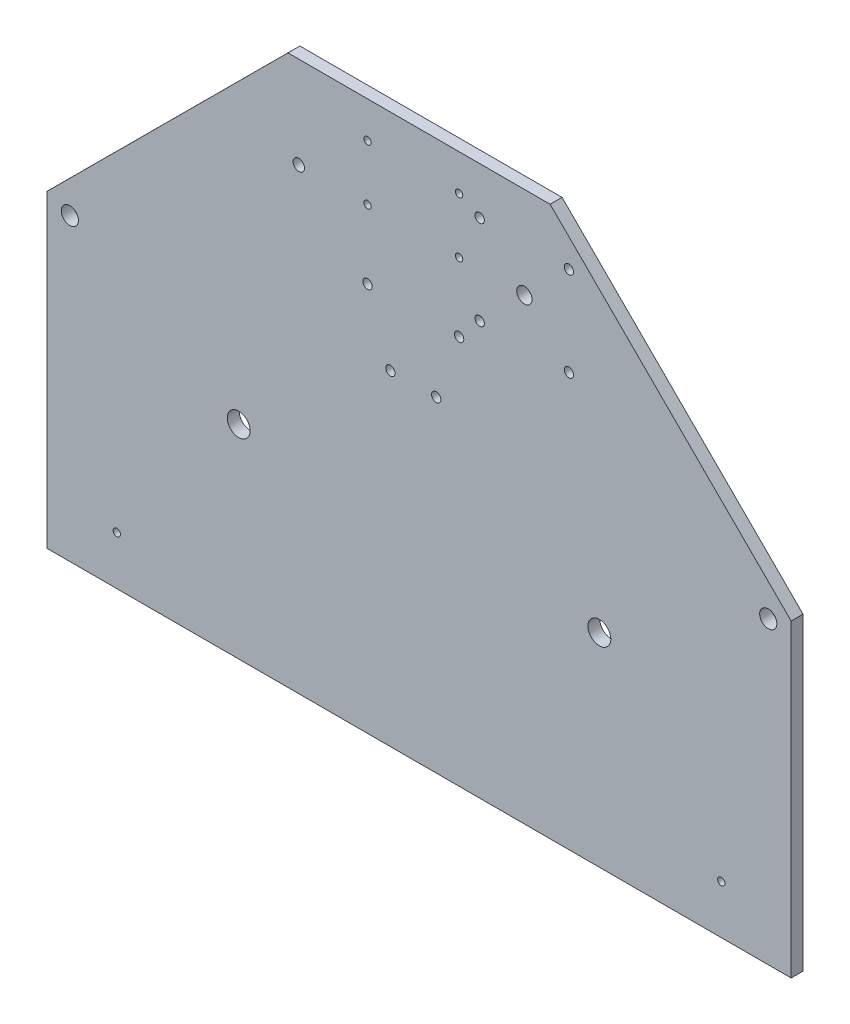
SolidWorks part; units mm, degrees
material "1060 Alloy"
ref_plane "Front Plane" through (0, 0, 0) normal (0, 0, 1) x (1, 0, 0)
ref_plane "Top Plane" through (0, 0, 0) normal (0, 1, 0) x (1, 0, 0)
ref_plane "Right Plane" through (0, 0, 0) normal (1, 0, 0) x (0, 0, -1)
sketch "reference" plane through (0, 0, 0) normal (0, 0, 1) x (1, 0, 0)
  line L0 (206.375, 0) -> (-206.375, 0)
  line L1 (-206.375, 0) -> (-206.375, 171.45)
  line L2 (-206.375, 171.45) -> (-72.7075, 304.8)
  line L3 (-72.7075, 304.8) -> (72.7075, 304.8)
  line L5 (206.375, 171.45) -> (72.7075, 304.8)
  line L6 (206.375, 0) -> (206.375, 171.45)
  circle A0 centre (-100.0125, 112.7125) radius 6.35
  circle A5 centre (100.0125, 112.7125) radius 6.35
  circle A6 centre (-66.675, 254) radius 3.175
  circle A7 centre (58.42, 254) radius 4.2545
  dimension "D10" = 106.3625
  dimension "D11" = 12.7
  dimension "D14" = 6.35
  dimension "D15" = 8.509
  dimension "D12" = 12.7
  dimension "D1" = 412.75
  dimension "D2" = 171.45
  dimension "D3" = 304.8
  dimension "D4" = 145.415
  dimension "D5" = 139.7
  dimension "D6" = 171.45
  dimension "D7" = 106.3625
  dimension "D8" = 112.7125
  dimension "D9" = 112.7125
  dimension "D13" = 50.8
  dimension "D16" = 50.8
  dimension "D17" = 125.095
extrude "Boss-Extrude3" add sketch "reference" along normal blind 6.604
hole_wizard "#10-32 Tapped Hole1" positions "Sketch2" profile "Sketch1" tap size "#10-32" standard "Ansi Inch" end condition through all
sketch "Sketch2" plane through (0, 0, 6.604) normal (0, 0, 1) x (1, 0, 0)
  line L0 (-206.375, 0) -> (206.375, 0) construction
  line L1 (-206.375, 171.45) -> (-206.375, 0) construction
  line L3 (206.375, 0) -> (206.375, 171.45) construction
  line L4 (72.7075, 304.8) -> (-72.7075, 304.8) construction
  line L9 (-66.675, 254) -> (-28.575, 254) construction
  point P0 (-167.64, 26.9875)
  point P1 (167.64, 27.0002)
  point P3 (-28.575, 284.734)
  point P5 (22.225, 284.734)
  point P7 (-28.575, 254)
  point P9 (22.225, 254)
  dimension "D1" = 26.9875
  dimension "D2" = 38.735
  dimension "D3" = 27.0002
  dimension "D4" = 38.735
  dimension "D5" = 20.066
  dimension "D6" = 50.8
  dimension "D7" = 38.1
cosmetic thread "Hole Thread1" parameters "D2"=4.826
cosmetic thread "Hole Thread2" parameters "D2"=4.826
cosmetic thread "Hole Thread3" parameters "D2"=4.826
cosmetic thread "Hole Thread4" parameters "D2"=4.826
cosmetic thread "Hole Thread5" parameters "D2"=4.826
cosmetic thread "Hole Thread6" parameters "D2"=4.826
sketch "Sketch1" plane through (-167.64, 26.9875, 6.604) normal (1, 0, 0) x (0, -1, 0)
  line L0 (0, 0) -> (0, 6.604)
  line L1 (0, 6.604) -> (2.0193, 6.604)
  line L2 (2.0193, 6.604) -> (2.0193, 0)
  line L5 (2.0193, 0) -> (0, 0)
  line L11 (0, -6.35) -> (0, 107.95) construction
  dimension "Thru Tap Drill Dia." = 4.0386
  dimension "Thru Tap Drill Depth" = 6.604
sketch "Sketch3" plane through (0, 0, 0) normal (0, 0, -1) x (-1, 0, 0)
  circle A0 centre (-33.6211, 278.7487) radius 2.5797
  circle A1 centre (-33.6211, 229.2513) radius 2.5797
  circle A2 centre (-83.1186, 229.2513) radius 2.5797
  circle A3 centre (-83.1186, 278.7487) radius 2.5797
  dimension "D1" = 5.1594
extrude "Cut-Extrude1" cut sketch "Sketch3" against normal through all
sketch "Sketch4" plane through (0, 0, 6.604) normal (0, 0, 1) x (1, 0, 0)
  line L0 (-28.575, 254) -> (-28.575, 215.9) construction
  line L1 (22.225, 254) -> (22.225, 215.9) construction
  circle A0 centre (-28.575, 215.9) radius 2.5797
  circle A1 centre (22.225, 215.9) radius 2.5797
  circle A4 centre (-15.875, 180.594) radius 2.5797
  circle A5 centre (9.525, 180.594) radius 2.5797
  dimension "D1" = 5.1594
  dimension "D4" = 5.1594
  dimension "D2" = 38.1
extrude "Cut-Extrude2" cut sketch "Sketch4" against normal through all
sketch "Sketch5" plane through (0, 0, 0) normal (0, 0, -1) x (-1, 0, 0)
  line L0 (-206.375, 171.45) -> (-72.7075, 304.8) construction
  line L1 (0, 304.8) -> (0, 0) construction
  line L2 (-72.7075, 304.8) -> (72.7075, 304.8) construction
  line L3 (-206.375, 0) -> (-206.375, 171.45) construction
  circle A0 centre (-193.675, 166.1806) radius 4.7625
  circle A1 centre (193.675, 166.1806) radius 4.7625
  circle A2 centre (-193.675, 166.1806) radius 12.7 construction
  circle A3 centre (-193.675, 166.1806) radius 12.7 construction
  dimension "D1" = 9.525
extrude "Cut-Extrude3" cut sketch "Sketch5" against normal through all
